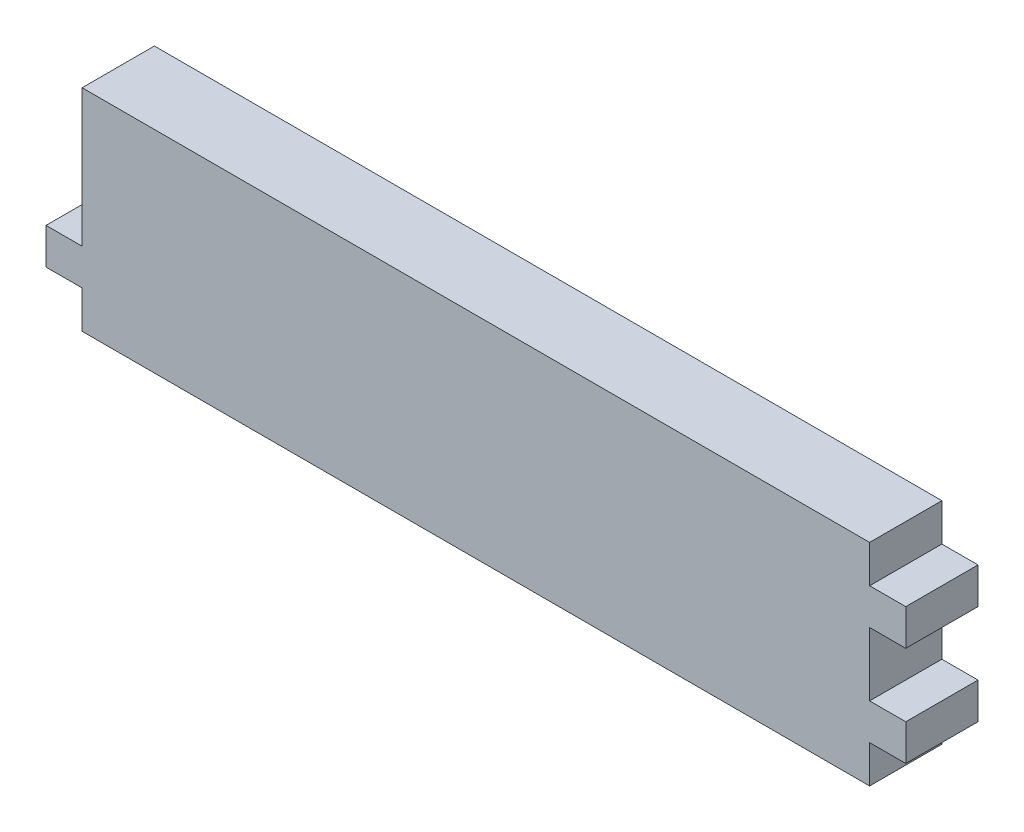
SolidWorks part; units mm, degrees
material "Balsa"
ref_plane "Front Plane" through (0, 0, 0) normal (0, 0, 1) x (1, 0, 0)
ref_plane "Top Plane" through (0, 0, 0) normal (0, 1, 0) x (1, 0, 0)
ref_plane "Right Plane" through (0, 0, 0) normal (1, 0, 0) x (0, 0, -1)
sketch "Sketch1" plane through (0, 0, 0) normal (0, 0, 1) x (1, 0, 0)
  line L0 (208.8644, -3.4799) -> (212.0394, -3.4799)
  line L2 (212.0394, -0.3049) -> (208.8644, -0.3049)
  line L3 (208.8644, -0.3049) -> (208.8644, 5.2831)
  line L4 (208.8644, 5.2831) -> (212.0394, 5.2831)
  line L5 (212.0394, 5.2831) -> (212.0394, 8.4581)
  line L6 (212.0394, 8.4581) -> (208.8644, 8.4581)
  line L7 (208.8644, -9.1826) -> (208.8644, 19.4913) construction
  line L8 (208.8644, -6.7819) -> (139.6494, -6.7819)
  line L9 (208.8644, 8.4581) -> (208.8644, 11.7601)
  line L10 (139.6494, -0.3049) -> (136.4744, -0.3049)
  line L11 (136.4744, -0.3049) -> (136.4744, -3.4799)
  line L12 (136.4744, -3.4799) -> (139.6494, -3.4799)
  line L13 (139.6494, -6.7819) -> (139.6494, -3.4799)
  line L14 (139.6494, -0.3049) -> (139.6494, 11.7601)
  line L15 (139.6494, 11.7601) -> (208.8644, 11.7601)
  line L16 (208.8644, -6.7819) -> (208.8644, -3.4799)
  line L17 (212.0394, -0.3049) -> (212.0394, -3.4799)
  point P18 (208.8644, 2.4891)
  point P19 (208.8644, 11.7601)
  point P20 (208.8644, -6.7819)
  dimension "D1" = 9.271
  dimension "D2" = 9.271
extrude "Boss-Extrude1" add sketch "Sketch1" along normal up to surface (6.35 mm away)
